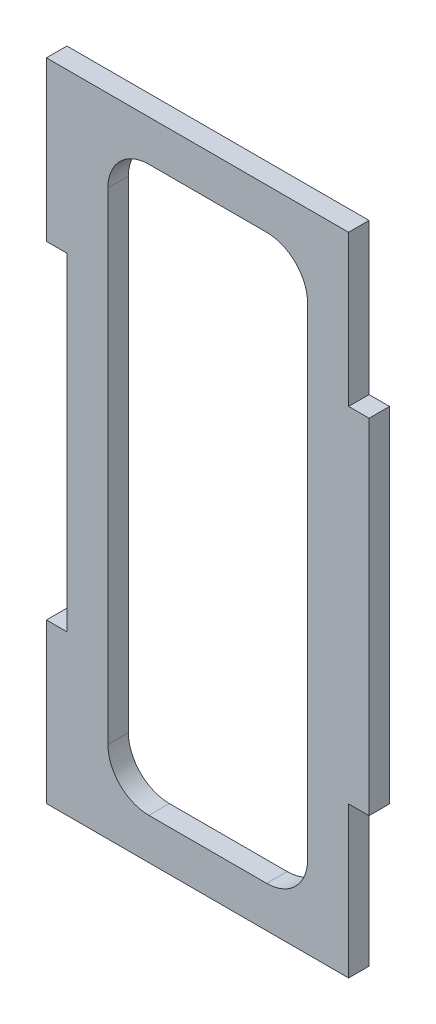
SolidWorks part; units mm, degrees
material "Acrylic (Medium-high impact)"
ref_plane "Front Plane" through (0, 0, 0) normal (0, 0, 1) x (1, 0, 0)
ref_plane "Top Plane" through (0, 0, 0) normal (0, 1, 0) x (1, 0, 0)
ref_plane "Right Plane" through (0, 0, 0) normal (1, 0, 0) x (0, 0, -1)
sketch "Sketch1" plane through (0, 0, 0) normal (0, 0, 1) x (1, 0, 0)
  line L1 (-50, -150.1518) -> (50, -150.1518)
  line L2 (-50, -150.1518) -> (-50, 50)
  line L3 (-50, 50) -> (50, 50)
  line L4 (50, -150.1518) -> (50, 50)
  dimension "D1" = 100
  dimension "D2" = 50
  dimension "D3" = 200.1518
  dimension "D4" = 50
extrude "Boss-Extrude1" add sketch "Sketch1" along normal blind 6.35
sketch "Sketch2" plane through (0, 0, 6.35) normal (0, 0, 1) x (1, 0, 0)
  line L0 (-43.65, 50) -> (-43.65, -150.1518) construction
  line L1 (50, 50) -> (-50, 50) construction
  line L2 (-50, -150.1518) -> (50, -150.1518) construction
  line L3 (-50, -50.0759) -> (50, -50.0759) construction
  line L4 (-50, 50) -> (-50, -150.1518) construction
  line L5 (50, -150.1518) -> (50, 50) construction
  line L6 (43.65, 50) -> (43.65, -150.1518) construction
  line L7 (-43.65, -50.0759) -> (-43.65, 50) construction
  line L8 (43.65, -50.0759) -> (43.65, 50) construction
  line L10 (-50, -50.0759) -> (-43.65, -50.0759)
  line L11 (-50, -50.0759) -> (-50, 0.7241)
  line L12 (-50, 0.7241) -> (-43.65, 0.7241)
  line L13 (-43.65, -50.0759) -> (-43.65, 0.7241)
  line L14 (-50, -50.0759) -> (-43.65, -50.0759)
  line L15 (-50, -50.0759) -> (-50, -100.8759)
  line L16 (-50, -100.8759) -> (-43.65, -100.8759)
  line L17 (-43.65, -50.0759) -> (-43.65, -100.8759)
  line L18 (43.65, 50) -> (50, 50)
  line L19 (43.65, 50) -> (43.65, 0.7241)
  line L20 (43.65, 0.7241) -> (50, 0.7241)
  line L21 (50, 50) -> (50, 0.7241)
  line L22 (43.65, -150.1518) -> (50, -150.1518)
  line L23 (43.65, -150.1518) -> (43.65, -100.8759)
  line L24 (43.65, -100.8759) -> (50, -100.8759)
  line L25 (50, -150.1518) -> (50, -100.8759)
  line M8 (-50, 50) -> (-50, -150.1518)
  line M9 (-50, -150.1518) -> (50, -150.1518)
  line M10 (50, -150.1518) -> (50, 50)
  line M11 (50, 50) -> (-50, 50)
  dimension "D1" = 6.35
  dimension "D2" = 6.35
  dimension "D3" = 100.0759
  dimension "D4" = 50.8
  dimension "D5" = 50.8
  dimension "D6" = 50.8
  dimension "D7" = 50.8
extrude "Cut-Extrude1" cut sketch "Sketch2" against normal blind 6.35 contours L10 L13 L12 M8 | L17 L10 L16 M8 | L19 L20 M10 M11 | L24 L23 M9 M10
sketch "Sketch3" plane through (0, 0, 6.35) normal (0, 0, 1) x (1, 0, 0)
  line L0 (-43.65, -100.8759) -> (-43.65, 0.7241) construction
  line L1 (-30.95, -137.4518) -> (30.95, -137.4518)
  line L2 (-30.95, -137.4518) -> (-30.95, 37.3)
  line L3 (-30.95, 37.3) -> (30.95, 37.3)
  line L4 (30.95, -137.4518) -> (30.95, 37.3)
  line L5 (43.65, 50) -> (-50, 50) construction
  line L6 (43.65, 50) -> (43.65, 0.7241) construction
  line L7 (-50, -150.1518) -> (43.65, -150.1518) construction
  dimension "D1" = 12.7
  dimension "D2" = 12.7
  dimension "D3" = 12.7
  dimension "D4" = 12.7
extrude "Cut-Extrude2" cut sketch "Sketch3" against normal blind 6.35
fillet "Fillet1" radius 12.7 4 edges at (30.95, -137.4518, 3.175) (30.95, 37.3, 3.175) (-30.95, 37.3, 3.175) (-30.95, -137.4518, 3.175)
sketch "Sketch6" plane through (0, 0.7241, 0) normal (0, 1, 0) x (1, 0, 0)
  line L1 (43.65, 0) -> (50, 0)
  line L2 (43.65, 0) -> (43.65, -6.35)
  line L3 (43.65, -6.35) -> (50, -6.35)
  line L4 (50, 0) -> (50, -6.35)
extrude "Boss-Extrude2" add sketch "Sketch6" along normal blind 2.54
sketch "Sketch7" plane through (0, -100.8759, 0) normal (0, -1, 0) x (1, 0, 0)
  line L1 (50, 6.35) -> (43.65, 6.35)
  line L2 (50, 6.35) -> (50, 0)
  line L3 (50, 0) -> (43.65, 0)
  line L4 (43.65, 6.35) -> (43.65, 0)
extrude "Boss-Extrude3" add sketch "Sketch7" along normal blind 2.54
sketch "Sketch10" plane through (0, 0, 6.35) normal (0, 0, 1) x (1, 0, 0)
  line L0 (-18.25, -137.4518) -> (18.25, -137.4518)
  line L1 (-50, 50) -> (43.65, 50)
  line L2 (-50, 50) -> (-50, 0.7241)
  line L3 (-50, -150.1518) -> (43.65, -150.1518)
  line L4 (43.65, -103.4159) -> (43.65, -150.1518)
  line L5 (-43.65, 0.7241) -> (-50, 0.7241)
  line L6 (-43.65, 0.7241) -> (-43.65, -100.8759)
  line L7 (-43.65, -100.8759) -> (-50, -100.8759)
  line L8 (43.65, 50) -> (43.65, 3.2641)
  line L9 (50, 3.2641) -> (43.65, 3.2641)
  line L10 (50, 3.2641) -> (50, -103.4159)
  line L11 (50, -103.4159) -> (43.65, -103.4159)
  line L12 (43.65, -103.4159) -> (43.65, -150.1518)
  line L13 (30.95, -124.7518) -> (30.95, 24.6)
  line L14 (18.25, 37.3) -> (-18.25, 37.3)
  line L15 (-30.95, 24.6) -> (-30.95, -124.7518)
  line L16 (-50, -100.8759) -> (-50, -150.1518)
  arc A0 (-18.25, 37.3) -> (-30.95, 24.6) centre (-18.25, 24.6) ccw
  arc A1 (18.25, 37.3) -> (30.95, 24.6) centre (18.25, 24.6) cw
  arc A2 (-30.95, -124.7518) -> (-18.25, -137.4518) centre (-18.25, -124.7518) ccw
  arc A3 (30.95, -124.7518) -> (18.25, -137.4518) centre (18.25, -124.7518) cw
